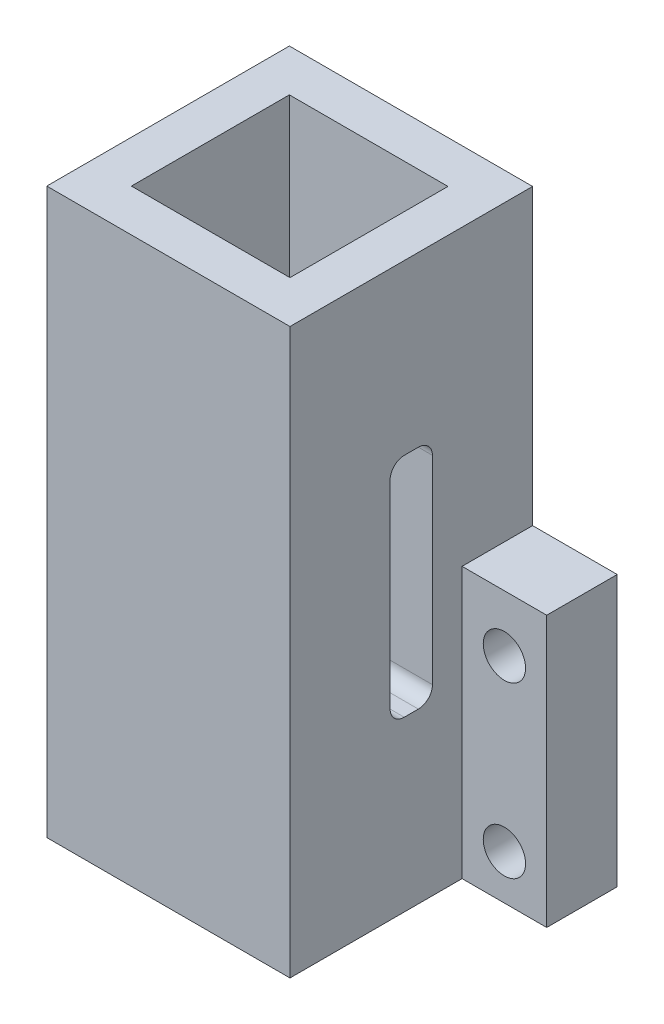
SolidWorks part; units mm, degrees
ref_plane "Front Plane" through (0, 0, 0) normal (0, 0, 1) x (1, 0, 0)
ref_plane "Top Plane" through (0, 0, 0) normal (0, 1, 0) x (1, 0, 0)
ref_plane "Right Plane" through (0, 0, 0) normal (1, 0, 0) x (0, 0, -1)
sketch "Plan" plane through (0, 0, 0) normal (0, 0, 1) x (1, 0, 0)
  line L0 (0, 0) -> (0, 60) construction
  line L1 (0, 0) -> (51.9615, -30) construction
  line L2 (0, 0) -> (-51.9615, -30) construction
  line L3 (0, 0) -> (0, 60) construction
  line L4 (0, 0) -> (51.9615, -30) construction
  line L5 (42.3527, 42.5) -> (-42.3527, 42.5) construction
  line L6 (-10, 60) -> (10, 60)
  line L7 (-10, 60) -> (-10, 25)
  line L8 (-10, 25) -> (10, 25)
  line L9 (10, 60) -> (10, 25)
  circle A0 centre (0, 0) radius 60
  text T0 "Tyre"
  point P13 (0, 60)
  point P17 (-10, 42.5)
  dimension "D1" = 3
  dimension "D5" = 120
  dimension "D2" = 120
  dimension "D3" = 35
  dimension "D4" = 20
sketch "Stepper Motor" plane through (0, 0, 0) normal (0, 0, 1) x (1, 0, 0)
  line L1 (10.7429, 49.5) -> (29.7429, 49.5)
  line L2 (10.7429, 49.5) -> (10.7429, 21.5)
  line L3 (10.7429, 21.5) -> (29.7429, 21.5)
  line L4 (29.7429, 49.5) -> (29.7429, 21.5)
  line L5 (10.7429, 47) -> (0.7429, 47)
  line L6 (10.7429, 47) -> (10.7429, 38)
  line L7 (10.7429, 38) -> (0.7429, 38)
  line L8 (0.7429, 47) -> (0.7429, 38)
  line L9 (-1.5598, 42.5) -> (29.7429, 42.5) construction
  line L11 (42.3527, 42.5) -> (-42.3527, 42.5) construction
  text T0 "Stepper"
  point P11 (0.7429, 42.5)
  dimension "D1" = 28
  dimension "D2" = 19
  dimension "D3" = 9
  dimension "D4" = 10
  dimension "D5" = 2.5
sketch "DC Motor" plane through (0, 0, 0) normal (0, 0, 1) x (1, 0, 0)
  line L0 (63.4697, 76.7537) -> (25.6249, 76.7537) construction
  line L1 (38.6689, 84.3037) -> (63.6689, 84.3037)
  line L2 (38.6689, 84.3037) -> (38.6689, 69.2037)
  line L3 (38.6689, 69.2037) -> (63.6689, 69.2037)
  line L4 (63.6689, 84.3037) -> (63.6689, 69.2037)
  line L5 (28.6689, 79.8287) -> (38.6689, 79.8287)
  line L6 (28.6689, 79.8287) -> (28.6689, 73.6787)
  line L7 (28.6689, 73.6787) -> (38.6689, 73.6787)
  line L8 (38.6689, 79.8287) -> (38.6689, 73.6787)
  text T0 "DC"
  point P10 (38.6689, 76.7537)
  point P11 (38.6689, 76.7537)
  dimension "D1" = 25
  dimension "D2" = 15.1
  dimension "D3" = 10
  dimension "D4" = 6.15
sketch "arm plan" plane through (0, 0, 0) normal (0, 0, 1) x (1, 0, 0)
  line L0 (0.8694, 39.0974) -> (0.8694, -9.5773) construction
  line L1 (-7.752, 39.0974) -> (9.4908, 39.0974)
  line L2 (-7.752, 39.0974) -> (-7.752, -9.5773)
  line L3 (-7.752, -9.5773) -> (9.4908, -9.5773)
  line L4 (9.4908, 39.0974) -> (9.4908, -9.5773)
  line L5 (-13.752, 9.5974) -> (15.4908, 9.5974)
  line L6 (-13.752, 9.5974) -> (-13.752, -9.5773)
  line L7 (-13.752, -9.5773) -> (15.4908, -9.5773)
  line L8 (15.4908, 9.5974) -> (15.4908, -9.5773)
  line L9 (0.8694, 9.5974) -> (0.8694, -9.5773) construction
  dimension "D1" = 48.6747
  dimension "D2" = 19.1747
  dimension "D3" = 29.2429
  dimension "D4" = 17.2429
sketch "Sketch7" plane through (0, 0, 0) normal (0, 0, 1) x (1, 0, 0)
  line L0 (9.4908, 39.0974) -> (9.4908, -9.5773) construction
  line L1 (-7.752, -9.5773) -> (9.4908, -9.5773)
  line L2 (-7.752, -9.5773) -> (-7.752, 30.4227)
  line L3 (-7.752, 30.4227) -> (9.4908, 30.4227)
  line L4 (9.4908, -9.5773) -> (9.4908, 30.4227)
  dimension "D1" = 40
extrude "Boss-Extrude1" add sketch "Sketch7" along normal blind 17.2
sketch "Sketch8" plane through (0, 0, 0) normal (0, 0, 1) x (1, 0, 0)
  line L1 (-13.752, 9.5974) -> (15.4908, 9.5974)
  line L2 (-13.752, 9.5974) -> (-13.752, -9.5773)
  line L3 (-13.752, -9.5773) -> (15.4908, -9.5773)
  line L4 (15.4908, 9.5974) -> (15.4908, -9.5773)
extrude "Boss-Extrude2" add sketch "Sketch8" along normal blind 5
ref_plane "Plane1" through (0, -9.5773, 0) normal (0, -1, 0) x (-1, 0, 0)
ref_plane "Plane2" through (0, 30.4227, 0) normal (0, 1, 0) x (1, 0, 0)
sketch "Sketch10" plane through (0, 30.4227, 0) normal (0, 1, 0) x (1, 0, 0)
  line L0 (-7.752, -8.6) -> (9.4908, -8.6) construction
  line L1 (-7.752, -17.2) -> (-7.752, 0) construction
  line L2 (9.4908, -17.2) -> (9.4908, 0) construction
  line L3 (-13.752, 0) -> (15.4908, 0) construction
  line L4 (-4.752, -3) -> (6.4908, -3)
  line L5 (-4.752, -3) -> (-4.752, -14.2)
  line L6 (-4.752, -14.2) -> (6.4908, -14.2)
  line L7 (6.4908, -3) -> (6.4908, -14.2)
  line L8 (-4.752, -3) -> (6.4908, -14.2) construction
  line L9 (-4.752, -14.2) -> (6.4908, -3) construction
  point P6 (0.8694, -8.6)
  dimension "D1" = 3
  dimension "D2" = 3
extrude "Cut-Extrude2" cut sketch "Sketch10" against normal blind 37
ref_plane "Plane3" through (-7.752, 0, 0) normal (-1, 0, 0) x (0, 0, 1)
sketch "Sketch11" plane through (-7.752, 0, 0) normal (-1, 0, 0) x (0, 0, 1)
  line L0 (17.2, 10.4227) -> (0, 10.4227) construction
  line L1 (17.2, 30.4227) -> (17.2, -9.5773) construction
  line L2 (0, 39.0974) -> (0, -9.5773) construction
  line L4 (7.1, 2.3838) -> (10.1, 2.3838)
  line L5 (7.1, 2.3838) -> (7.1, 18.4617)
  line L6 (7.1, 18.4617) -> (10.1, 18.4617)
  line L7 (10.1, 2.3838) -> (10.1, 18.4617)
  line L8 (7.1, 2.3838) -> (10.1, 18.4617) construction
  line L9 (7.1, 18.4617) -> (10.1, 2.3838) construction
  point P6 (8.6, 10.4227)
  dimension "D1" = 3
extrude "Cut-Extrude3" cut sketch "Sketch11" against normal up to surface (17.2429 mm away) up to face at (9.4908, 10.1476, 7.4)
fillet "Fillet1" radius 1 8 edges at (-6.252, 2.3838, 10.1) (-6.252, 18.4617, 10.1) (-6.252, 2.3838, 7.1) (-6.252, 18.4617, 7.1) (7.9908, 18.4617, 10.1) (7.9908, 18.4617, 7.1) (7.9908, 2.3838, 10.1) (7.9908, 2.3838, 7.1)
sketch "Sketch12" plane through (0, 0, 0) normal (0, 0, 1) x (1, 0, 0)
  line L0 (-13.752, 9.5974) -> (15.4908, 9.5974) construction
  line L1 (-13.752, 9.5974) -> (-13.752, -9.5773) construction
  line L2 (-13.752, -9.5773) -> (15.4908, -9.5773) construction
  line L4 (0.8694, -9.5773) -> (0.8694, 9.5974) construction
  circle A0 centre (-10.752, 5.5974) radius 1.5
  circle A1 centre (-10.752, -6.4115) radius 1.5
  circle A2 centre (12.4908, -6.4115) radius 1.5
  circle A3 centre (12.4908, 5.5974) radius 1.5
  dimension "D1" = 4
  dimension "D4" = 3
  dimension "D5" = 3
  dimension "D2" = 3
  dimension "D3" = 3.1658
extrude "Cut-Extrude4" cut sketch "Sketch12" along normal up to surface (5 mm away) up to face at (-10.752, 0.0101, 5)
